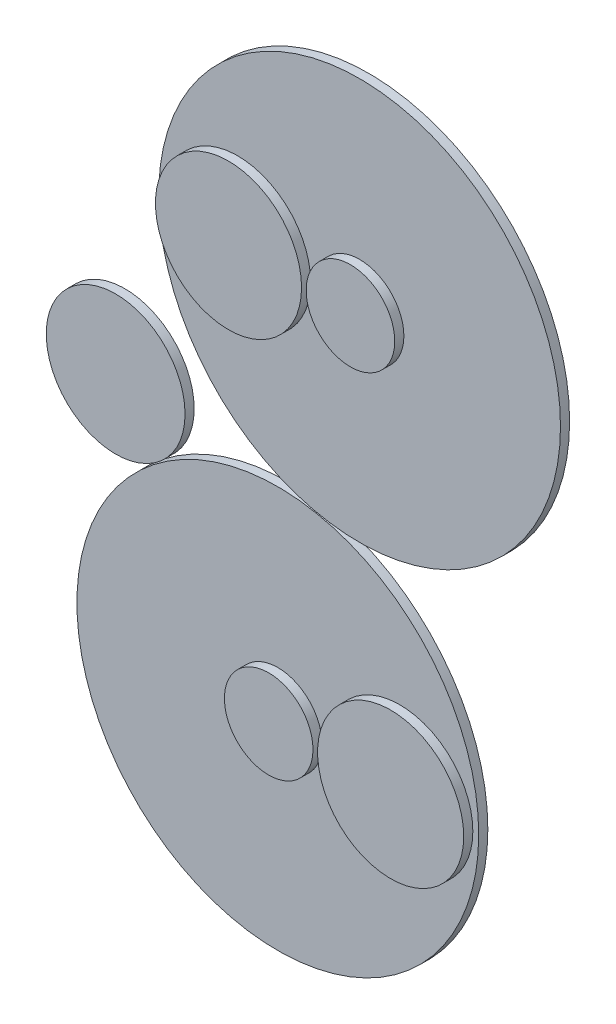
SolidWorks part; units mm, degrees
ref_plane "Plano frontal" through (0, 0, 0) normal (0, 0, 1) x (1, 0, 0)
ref_plane "Plano superior" through (0, 0, 0) normal (0, 1, 0) x (1, 0, 0)
ref_plane "Plano direito" through (0, 0, 0) normal (1, 0, 0) x (0, 0, -1)
sketch "Esboço1" plane through (0, 0, 0) normal (0, 0, 1) x (1, 0, 0)
  line L0 (0, 0) -> (8.954, 43.1814) construction
  line L1 (8.954, 43.1814) -> (-4.401, 43.1814) construction
  line L2 (0, 0) -> (13.355, 0) construction
  line L3 (4.477, -5.5513) -> (4.477, 54.3612) construction
  circle A0 centre (0, 0) radius 44.1 construction
  circle A1 centre (0, 0) radius 29.7 construction
  circle A2 centre (8.954, 43.1814) radius 33 construction
  dimension "D1" = 4.477
  dimension "D2" = 4.477
sketch "Esboço2" plane through (0, 0, 0) normal (0, 0, 1) x (1, 0, 0)
  circle A0 centre (0, 0) radius 22
  circle A1 centre (8.954, 43.1814) radius 22
  circle A2 centre (-17.7589, 23.8057) radius 7.6
  circle A3 centre (0, 0) radius 29.7 construction
  circle A4 centre (8.954, 43.1814) radius 33 construction
extrude "Ressalto-extrusão1" add sketch "Esboço2" along normal blind 1 contours A0 | A1 | A2
sketch "Esboço3" plane through (0, 0, 1) normal (0, 0, 1) x (1, 0, 0)
  circle A0 centre (8.954, 43.1814) radius 4.85
  circle A1 centre (0, 0) radius 4.85
  circle A2 centre (-4.401, 43.1814) radius 8
  circle A3 centre (13.355, 0) radius 8
extrude "Ressalto-extrusão2" add sketch "Esboço3" along normal blind 1
